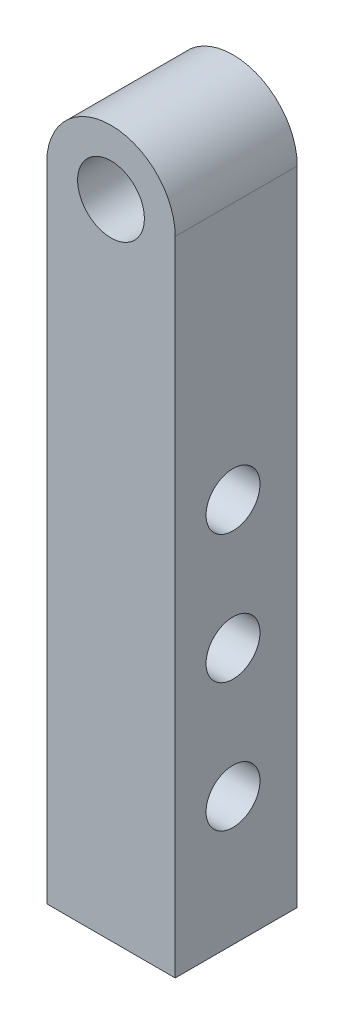
SolidWorks part; units mm, degrees
ref_plane "前视基准面" through (0, 0, 0) normal (0, 0, 1) x (1, 0, 0)
ref_plane "上视基准面" through (0, 0, 0) normal (0, 1, 0) x (1, 0, 0)
ref_plane "右视基准面" through (0, 0, 0) normal (1, 0, 0) x (0, 0, -1)
sketch "草图1" plane through (0, 0, 0) normal (0, 0, 1) x (1, 0, 0)
  line L0 (-5, 0) -> (-5, -50)
  line L1 (-5, -50) -> (5, -50)
  line L2 (5, -50) -> (5, 0)
  arc A0 (5, 0) -> (-5, 0) centre (0, 0) ccw
  circle A1 centre (0, 0) radius 2.6
  dimension "D1" = 10
  dimension "D2" = 5.2
  dimension "D3" = 50
extrude "凸台-拉伸1" add sketch "草图1" along normal blind 9.5
sketch "草图2" plane through (-5, 0, 0) normal (-1, 0, 0) x (0, 0, 1)
  line L0 (0, 0) -> (0, -50) construction
  line L3 (9.5, 0) -> (0, 0) construction
  circle A0 centre (5, -20) radius 2.1
  circle A1 centre (5, -30) radius 2.1
  circle A2 centre (5, -40) radius 2.1
  dimension "D1" = 4.2
  dimension "D2" = 5
  dimension "D3" = 20
  dimension "D4" = 3
extrude "切除-拉伸1" cut sketch "草图2" against normal blind 10
